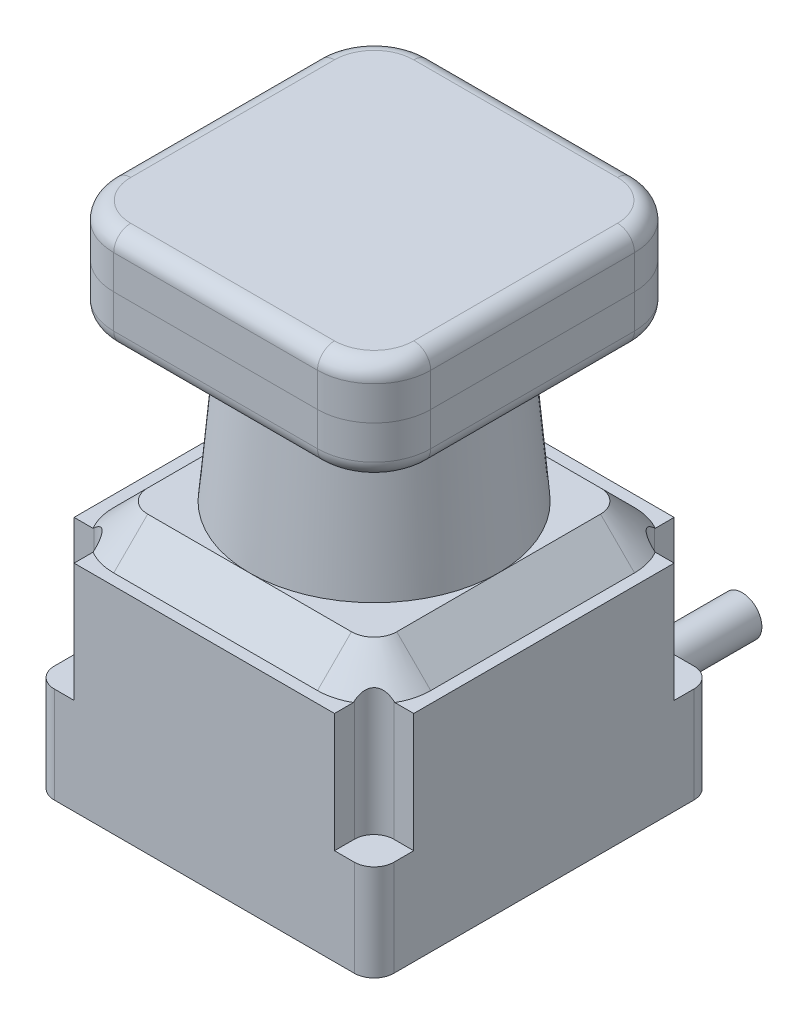
SolidWorks part; units mm, degrees
ref_plane "Front Plane" through (0, 0, 0) normal (0, 0, 1) x (1, 0, 0)
ref_plane "Top Plane" through (0, 0, 0) normal (0, 1, 0) x (1, 0, 0)
ref_plane "Right Plane" through (0, 0, 0) normal (1, 0, 0) x (0, 0, -1)
sketch "Sketch1" plane through (0, 0, 0) normal (0, 1, 0) x (1, 0, 0)
  line L1 (-26.5, -30) -> (26.5, -30)
  line L2 (-30, -26.5) -> (-30, 26.5)
  line L3 (-26.5, 30) -> (26.5, 30)
  line L4 (30, -26.5) -> (30, 26.5)
  line L5 (-30, -30) -> (30, 30) construction
  line L6 (-30, 30) -> (30, -30) construction
  arc A0 (-26.5, -30) -> (-30, -26.5) centre (-26.5, -26.5) cw
  arc A1 (26.5, -30) -> (30, -26.5) centre (26.5, -26.5) ccw
  arc A2 (30, 26.5) -> (26.5, 30) centre (26.5, 26.5) ccw
  arc A3 (-26.5, 30) -> (-30, 26.5) centre (-26.5, 26.5) ccw
  point P0 (0, 0)
  dimension "D3" = 3.5
  dimension "D1" = 60
  dimension "D2" = 60
extrude "Boss-Extrude1" add sketch "Sketch1" along normal blind 38
sketch "Sketch2" plane through (0, 38, 0) normal (0, 1, 0) x (1, 0, 0)
  line L1 (-18, -28) -> (18, -28)
  line L2 (-28, -18) -> (-28, 18)
  line L3 (-18, 28) -> (18, 28)
  line L4 (28, -18) -> (28, 18)
  line L5 (-28, -28) -> (28, 28) construction
  line L6 (-28, 28) -> (28, -28) construction
  arc A0 (18, -28) -> (28, -18) centre (18, -18) ccw
  arc A1 (18, 28) -> (28, 18) centre (18, 18) cw
  arc A2 (-28, 18) -> (-18, 28) centre (-18, 18) cw
  arc A3 (-18, -28) -> (-28, -18) centre (-18, -18) cw
  point P0 (0, 0)
  dimension "D2" = 10
  dimension "D1" = 56
extrude "Boss-Extrude2" add sketch "Sketch2" along normal blind 6 draft 45
sketch "Sketch3" plane through (0, 38, 0) normal (0, 1, 0) x (1, 0, 0)
  line L0 (23, -26.5) -> (23, -30)
  line L1 (-26.5, -30) -> (26.5, -30) construction
  line L2 (26.5, -23) -> (30, -23)
  line L3 (30, -26.5) -> (30, 26.5) construction
  arc A0 (26.5, -23) -> (23, -26.5) centre (26.5, -26.5) ccw
  arc A7 (26.5, -30) -> (30, -26.5) centre (26.5, -26.5) ccw construction
  line M2 (-26.5, -30) -> (26.5, -30)
  arc M3 (26.5, -30) -> (30, -26.5) centre (26.5, -26.5) ccw
  line M4 (30, -26.5) -> (30, 26.5)
  arc M9 (28, -18) -> (18, -28) centre (18, -18) cw
extrude "Cut-Extrude3" cut sketch "Sketch3" against normal blind 21 and the other way through all contours L2 L0 M9 M2 M3 M4 | L2 A0 L0 M9
ref_axis "Axis1" through (0, -2.2, 0) along (0, 1, 0)
pattern_circular "CirPattern1" count 4 every 90 about axis through (0, 0, 0) along (0, 1, 0) of "Cut-Extrude3"
sketch "Sketch4" plane through (0, 0, 0) normal (0, 0, 1) x (1, 0, 0)
  line L0 (0, 44) -> (0, 72)
  line L1 (0, 72) -> (19.5503, 72)
  line L2 (19.5503, 72) -> (22, 44)
  line L3 (0, 44) -> (22, 44)
  dimension "D1" = 28
  dimension "D2" = 5
revolve "Revolve1" add sketch "Sketch4" angle 360 about axis through (0, -2.2, 0) along (0, 1, 0)
sketch "Sketch5" plane through (0, 0, -30) normal (0, 0, -1) x (-1, 0, 0)
  line L0 (0, -2.2) -> (0, 46.2) construction
  line L1 (-26.5, 0) -> (26.5, 0) construction
  line L2 (0, 0) -> (0, 30.392) construction
  circle A0 centre (-15, 9) radius 3.5
  circle A1 centre (15, 9) radius 3.5
  dimension "D1" = 7
  dimension "D3" = 9
  dimension "D2" = 15
extrude "Boss-Extrude3" add sketch "Sketch5" along normal blind 20
sketch "Sketch6" plane through (0, 72, 0) normal (0, 1, 0) x (1, 0, 0)
  line L1 (-18, -28) -> (18, -28)
  line L2 (-28, -18) -> (-28, 18)
  line L3 (-18, 28) -> (18, 28)
  line L4 (28, -18) -> (28, 18)
  line L5 (-28, -28) -> (28, 28) construction
  line L6 (-28, 28) -> (28, -28) construction
  line L8 (18, 28) -> (-18, 28) construction
  line L9 (28, -18) -> (28, 18) construction
  arc A0 (28, -18) -> (18, -28) centre (18, -18) cw
  arc A1 (-18, -28) -> (-28, -18) centre (-18, -18) cw
  arc A2 (-18, 28) -> (-28, 18) centre (-18, 18) ccw
  arc A3 (18, 28) -> (28, 18) centre (18, 18) cw
  point P0 (0, 0)
  dimension "D1" = 10
extrude "Boss-Extrude4" add sketch "Sketch6" along normal blind 18
fillet "Fillet1" radius 3 16 edges at (-28, 72, 0) (-25.0711, 72, -25.0711) (0, 72, -28) (25.0711, 72, -25.0711) (28, 72, 0) (25.0711, 72, 25.0711) (0, 72, 28) (25.0711, 90, 25.0711) (0, 90, 28) (-25.0711, 90, 25.0711) (-28, 90, 0) (-25.0711, 90, -25.0711) (0, 90, -28) (25.0711, 90, -25.0711) (-25.0711, 72, 25.0711) (28, 90, 0)
ref_plane "Plane1" through (0, 81, 0) normal (0, 1, 0) x (1, 0, 0)
split line "Split Line2"
